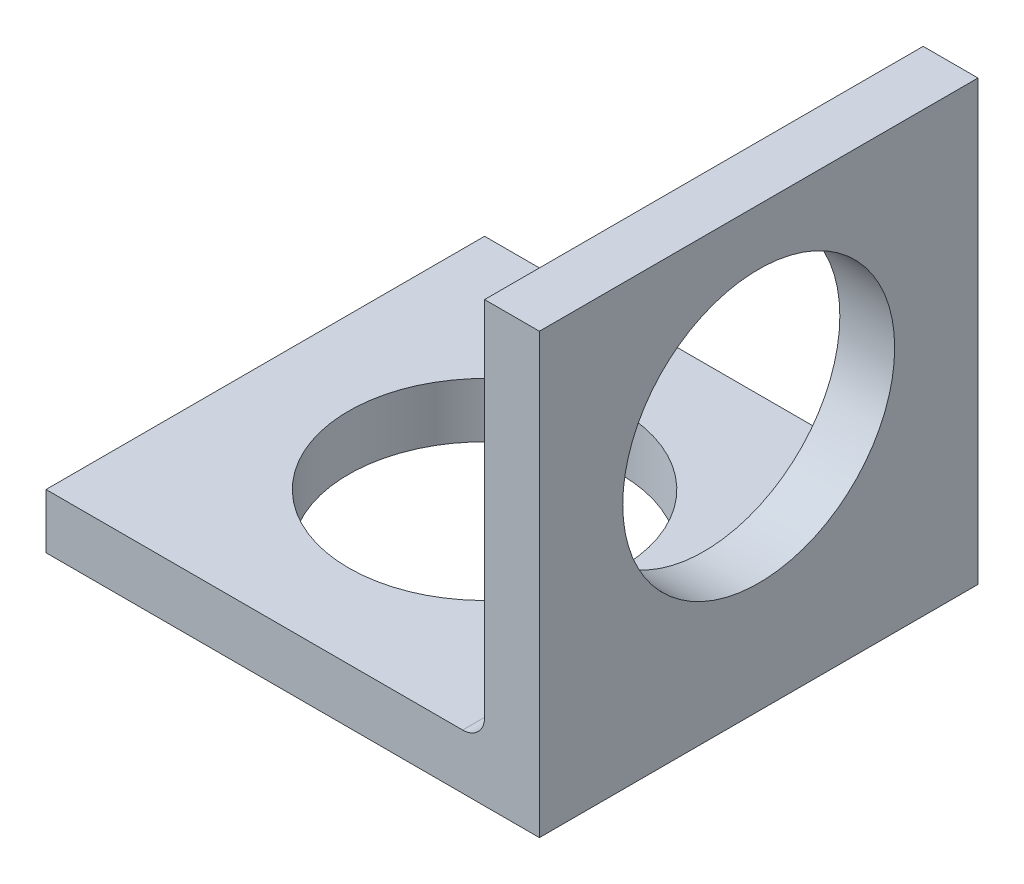
SolidWorks part; units mm, degrees
ref_plane "Front Plane" through (0, 0, 0) normal (0, 0, 1) x (1, 0, 0)
ref_plane "Top Plane" through (0, 0, 0) normal (0, 1, 0) x (1, 0, 0)
ref_plane "Right Plane" through (0, 0, 0) normal (1, 0, 0) x (0, 0, -1)
sketch "Sketch1" plane through (0, 0, 0) normal (0, 0, 1) x (1, 0, 0)
  line L0 (0, 0) -> (14.2875, 0)
  line L1 (14.2875, 0) -> (14.2875, 12.7)
  line L2 (0, 0) -> (0, 1.5875)
  line L3 (0, 1.5875) -> (12.7, 1.5875)
  line L4 (12.7, 1.5875) -> (12.7, 12.7)
  line L5 (12.7, 12.7) -> (14.2875, 12.7)
  dimension "D1" = 12.7
  dimension "D2" = 14.2875
  dimension "D3" = 1.5875
  dimension "D4" = 1.5875
extrude "Boss-Extrude1" add sketch "Sketch1" along normal blind 12.7
sketch "Sketch2" plane through (12.7, 0, 0) normal (-1, 0, 0) x (0, 0, 1)
  line L0 (6.35, 12.7) -> (6.35, 1.5875) construction
  line L1 (12.7, 12.7) -> (0, 12.7) construction
  line L2 (12.7, 1.5875) -> (0, 1.5875) construction
  line L3 (0, 7.1438) -> (12.7, 7.1437) construction
  line L4 (0, 12.7) -> (0, 1.5875) construction
  line L5 (12.7, 12.7) -> (12.7, 1.5875) construction
  circle A0 centre (6.35, 7.1438) radius 3.937
  dimension "D1" = 7.874
extrude "Cut-Extrude1" cut sketch "Sketch2" against normal blind 6.35
sketch "Sketch4" plane through (0, 1.5875, 0) normal (0, 1, 0) x (1, 0, 0)
  line L0 (6.35, 0) -> (6.35, -12.7) construction
  line L1 (12.7, 0) -> (0, 0) construction
  line L2 (12.7, -12.7) -> (0, -12.7) construction
  line L3 (0, -6.35) -> (12.7, -6.35) construction
  line L4 (0, -12.7) -> (0, 0) construction
  line L5 (12.7, -12.7) -> (12.7, 0) construction
  circle A0 centre (6.35, -6.35) radius 3.937
  dimension "D1" = 7.874
extrude "Cut-Extrude2" cut sketch "Sketch4" against normal blind 6.35
fillet "Fillet2" radius 0.635 1 edges at (12.7, 1.5875, 6.35)
